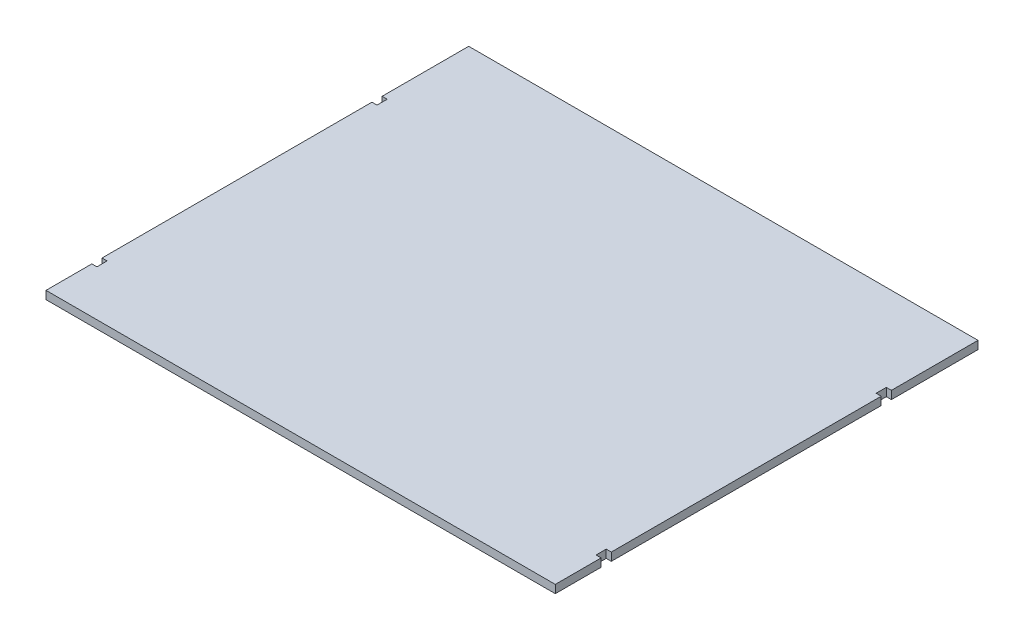
SolidWorks part; units mm, degrees
ref_plane "Front Plane" through (0, 0, 0) normal (0, 0, 1) x (1, 0, 0)
ref_plane "Top Plane" through (0, 0, 0) normal (0, 1, 0) x (1, 0, 0)
ref_plane "Right Plane" through (0, 0, 0) normal (1, 0, 0) x (0, 0, -1)
sketch "Sketch1" plane through (0, 0, 0) normal (0, 1, 0) x (1, 0, 0)
  line L0 (0, 9) -> (1, 9)
  line L1 (0, 0) -> (100, 0)
  line L2 (0, 0) -> (0, 9)
  line L3 (0, 83) -> (100, 83)
  line L4 (100, 0) -> (100, 9)
  line L5 (1, 9) -> (1, 11)
  line L6 (1, 11) -> (0, 11)
  line L7 (100, 9) -> (99, 9)
  line L8 (99, 9) -> (99, 11)
  line L9 (99, 11) -> (100, 11)
  line L10 (0, 64) -> (1, 64)
  line L11 (1, 64) -> (1, 66)
  line L12 (1, 66) -> (0, 66)
  line L13 (100, 66) -> (99, 66)
  line L14 (99, 66) -> (99, 64)
  line L15 (99, 64) -> (100, 64)
  line L16 (0, 66) -> (0, 83)
  line L17 (0, 11) -> (0, 64)
  line L18 (100, 66) -> (100, 83)
  line L19 (100, 11) -> (100, 64)
extrude "Boss-Extrude1" add sketch "Sketch1" along normal blind 1.5875
